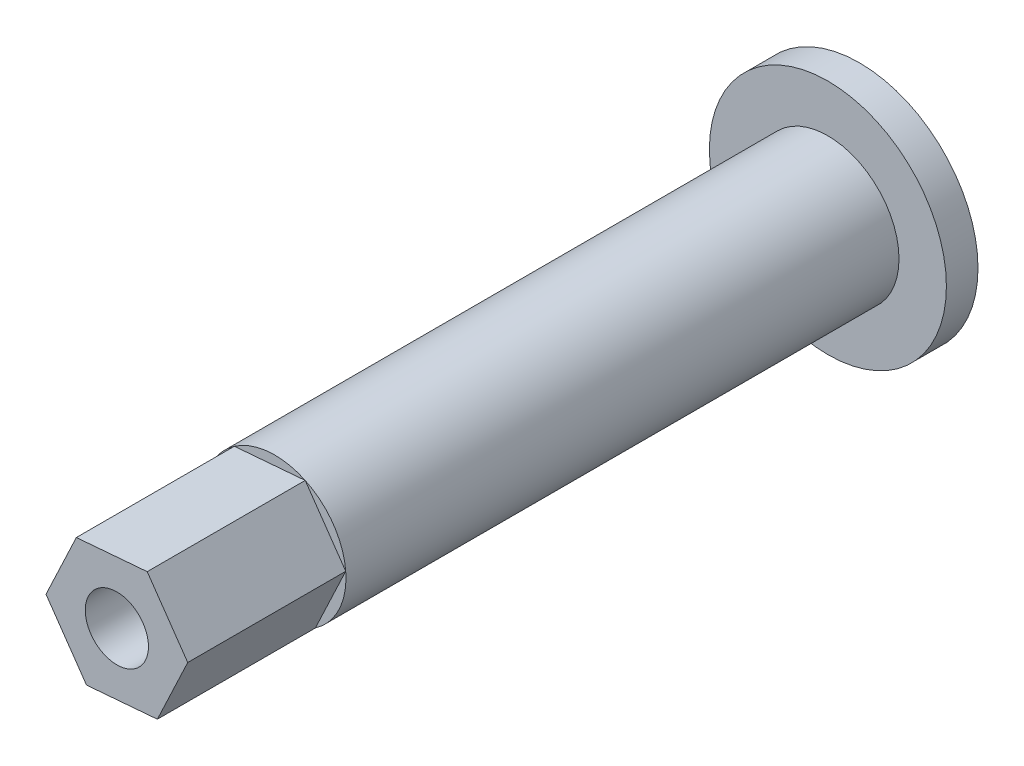
SolidWorks part; units mm, degrees
ref_plane "Front Plane" through (0, 0, 0) normal (0, 0, 1) x (1, 0, 0)
ref_plane "Top Plane" through (0, 0, 0) normal (0, 1, 0) x (1, 0, 0)
ref_plane "Right Plane" through (0, 0, 0) normal (1, 0, 0) x (0, 0, -1)
sketch "Sketch1" plane through (0, 0, 0) normal (0, 0, 1) x (1, 0, 0)
  line L0 (-1.85, 1.9666) -> (-1.85, -1.9666)
  line L1 (1.85, 1.9666) -> (1.85, -1.9666)
  circle A0 centre (0, 0) radius 4.5
  arc A2 (1.8521, 1.9646) -> (1.85, 1.9666) centre (0, 0) ccw
  arc A3 (-1.85, 1.9666) -> (1.8521, 1.9646) centre (0, 0) cw
  arc A4 (1.85, -1.9666) -> (-1.85, -1.9666) centre (0, 0) cw
  dimension "D1" = 9
  dimension "D2" = 3.7
  dimension "D3" = 1.85
extrude "Boss-Extrude1" add sketch "Sketch1" along normal blind 10
sketch "Sketch2" plane through (0, 0, 0) normal (0, 0, -1) x (-1, 0, 0)
  line L0 (-1.85, 1.9666) -> (-1.85, -1.9666) construction
  line L1 (1.85, 1.9666) -> (1.85, -1.9666) construction
  line L2 (1.85, 1.9666) -> (1.85, -1.9666)
  line L3 (-1.85, 1.9666) -> (-1.85, -1.9666)
  circle A0 centre (0, 0) radius 7.5
  arc A1 (1.85, 1.9666) -> (-1.85, 1.9666) centre (0, 0) ccw construction
  arc A2 (-1.85, -1.9666) -> (1.85, -1.9666) centre (0, 0) ccw construction
  arc A3 (-1.85, -1.9666) -> (1.85, -1.9666) centre (0, 0) ccw
  arc A4 (1.85, 1.9666) -> (-1.85, 1.9666) centre (0, 0) ccw
extrude "Boss-Extrude2" add sketch "Sketch2" along normal blind 2 contours A0
sketch "Sketch3" plane through (0, 0, 10) normal (0, 0, 1) x (1, 0, 0)
  circle A0 centre (0, 0) radius 4.5
extrude "Boss-Extrude3" add sketch "Sketch3" along normal blind 25
sketch "Sketch4" plane through (0, 0, 35) normal (0, 0, 1) x (1, 0, 0)
  line L1 (1.9208, 4.0695) -> (-2.5639, 3.6982)
  line L2 (-2.5639, 3.6982) -> (-4.4847, -0.3713)
  line L3 (-4.4847, -0.3713) -> (-1.9208, -4.0695)
  line L4 (-1.9208, -4.0695) -> (2.5639, -3.6982)
  line L5 (2.5639, -3.6982) -> (4.4847, 0.3713)
  line L6 (4.4847, 0.3713) -> (1.9208, 4.0695)
  circle A0 centre (0, 0) radius 3.8971 construction
extrude "Boss-Extrude4" add sketch "Sketch4" along normal blind 10
sketch "Sketch5" plane through (0, 0, 45) normal (0, 0, 1) x (1, 0, 0)
  circle A0 centre (0, 0) radius 2
extrude "Cut-Extrude1" cut sketch "Sketch5" against normal blind 6
